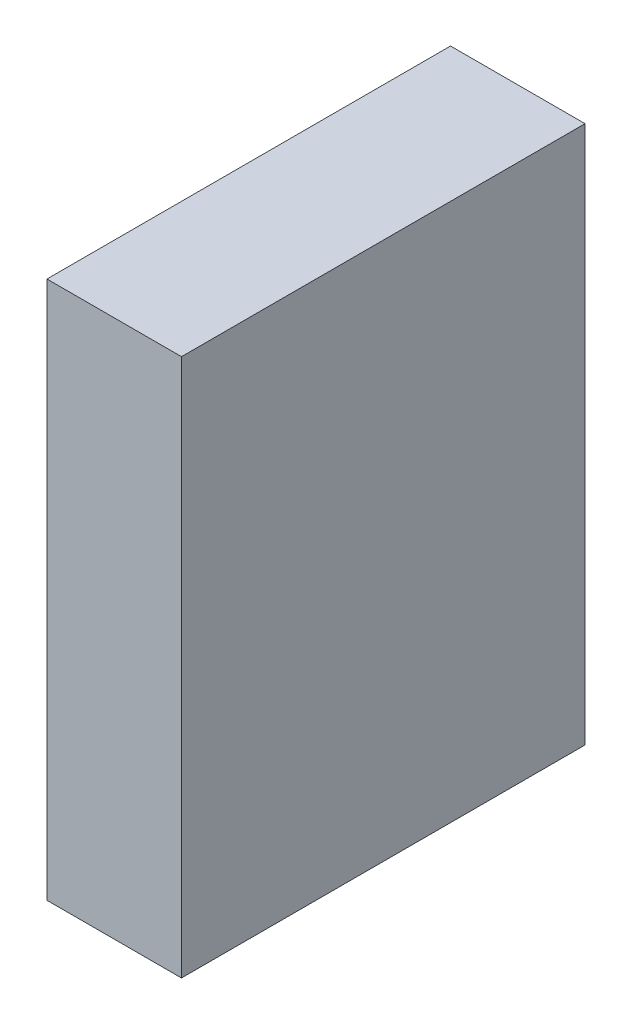
SolidWorks part; units mm, degrees
ref_plane "Front Plane" through (0, 0, 0) normal (1, 0, 0) x (0, 1, 0)
ref_plane "Top Plane" through (0, 0, 0) normal (0, 0, 1) x (0, 1, 0)
ref_plane "Right Plane" through (0, 0, 0) normal (0, 1, 0) x (-1, 0, 0)
sketch "Sketch1" plane through (0, 0, 0) normal (0, 0, 1) x (0, 1, 0)
  line L1 (-500, -125) -> (500, -125)
  line L2 (-500, -125) -> (-500, 125)
  line L3 (-500, 125) -> (500, 125)
  line L4 (500, -125) -> (500, 125)
  line L5 (-500, -125) -> (500, 125) construction
  line L6 (-500, 125) -> (500, -125) construction
  point P0 (0, 0)
  dimension "D1" = 1000
  dimension "D2" = 250
extrude "Boss-Extrude1" add sketch "Sketch1" along normal blind 750
